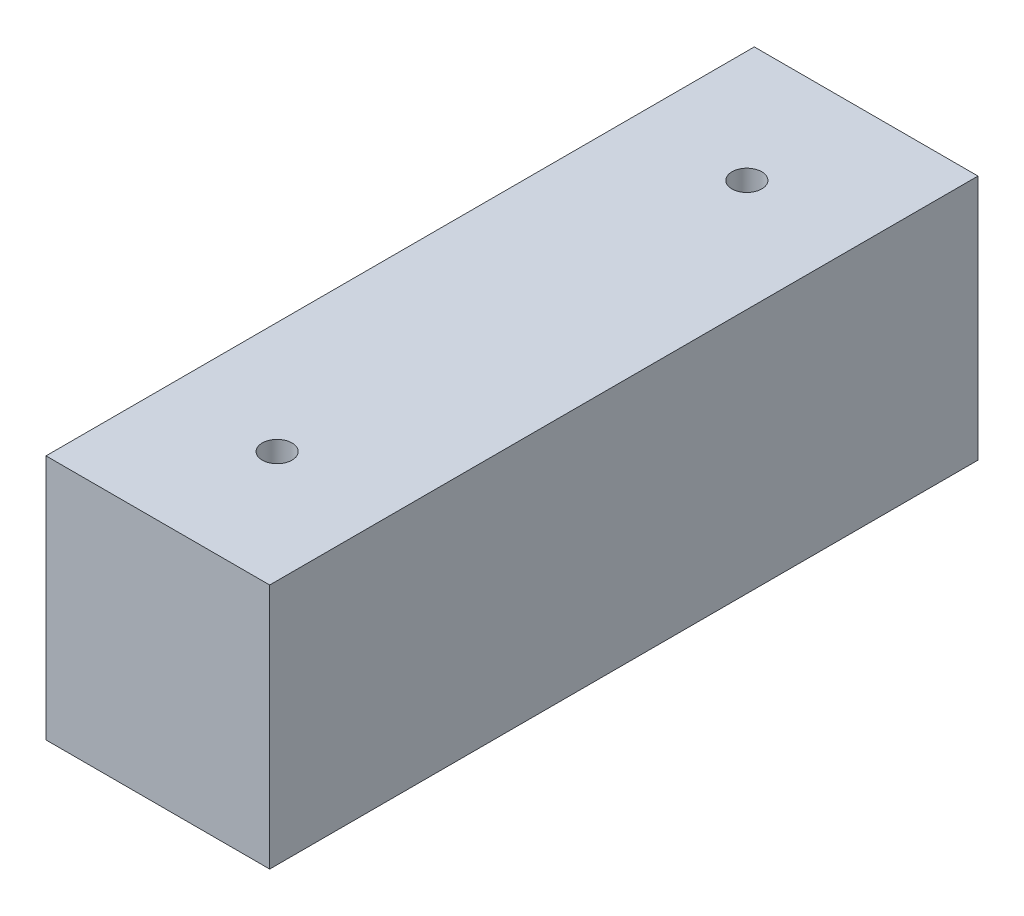
SolidWorks part; units mm, degrees
ref_plane "Alzado" through (0, 0, 0) normal (0, 0, 1) x (1, 0, 0)
ref_plane "Planta" through (0, 0, 0) normal (0, 1, 0) x (1, 0, 0)
ref_plane "Vista lateral" through (0, 0, 0) normal (1, 0, 0) x (0, 0, -1)
sketch "Croquis1" plane through (0, 0, 0) normal (0, 0, 1) x (1, 0, 0)
  line L1 (15, -16.5) -> (-15, -16.5)
  line L2 (15, -16.5) -> (15, 16.5)
  line L3 (15, 16.5) -> (-15, 16.5)
  line L4 (-15, -16.5) -> (-15, 16.5)
  line L5 (15, -16.5) -> (-15, 16.5) construction
  line L6 (15, 16.5) -> (-15, -16.5) construction
  point P0 (0, 0)
extrude "Saliente-Extruir1" add sketch "Croquis1" against normal blind 95
sketch "Croquis2" plane through (0, 16.5, 0) normal (0, 1, 0) x (1, 0, 0)
  line L0 (-15, 47.5) -> (15, 47.5) construction
  line L1 (-15, 95) -> (-15, 0) construction
  line L2 (15, 95) -> (15, 0) construction
  line L3 (0, 0) -> (0, 16) construction
  circle A0 centre (0, 16) radius 2
  circle A1 centre (0, 79) radius 2
extrude "Cortar-Extruir1" cut sketch "Croquis2" against normal blind 5
